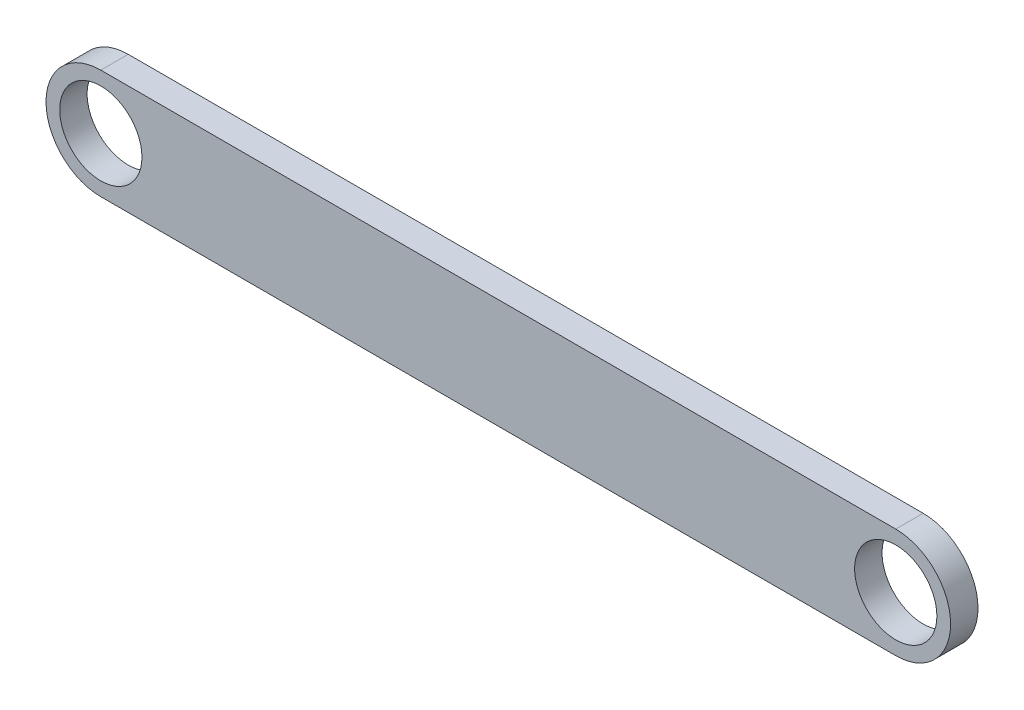
SolidWorks part; units mm, degrees
ref_plane "Спереди" through (0, 0, 0) normal (0, 0, 1) x (1, 0, 0)
ref_plane "Сверху" through (0, 0, 0) normal (0, 1, 0) x (1, 0, 0)
ref_plane "Справа" through (0, 0, 0) normal (1, 0, 0) x (0, 0, -1)
other "Configuration Table"
sketch "Эскиз1" plane through (0, 0, 0) normal (0, 0, 1) x (1, 0, 0)
  line L0 (0, 0) -> (290, 0) construction
  line L1 (0, 20) -> (290, 20)
  line L2 (0, -20) -> (290, -20)
  arc A0 (0, 20) -> (0, -20) centre (0, 0) ccw
  arc A1 (290, -20) -> (290, 20) centre (290, 0) ccw
  circle A2 centre (0, 0) radius 15
  circle A3 centre (290, 0) radius 15
  point P3 (145, 0)
  dimension "D3" = 30
  dimension "D4" = 30
  dimension "D1" = 290
  dimension "D2" = 40
extrude "Бобышка-Вытянуть1" add sketch "Эскиз1" along normal blind 10
